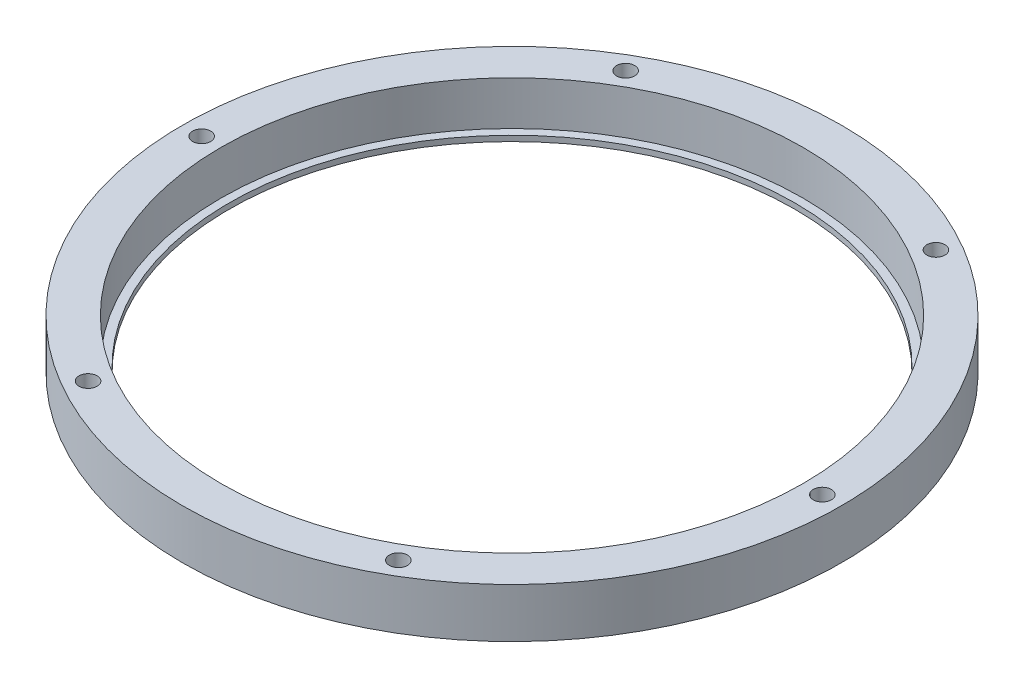
SolidWorks part; units mm, degrees
material "6061 合金"
ref_plane "前视基准面" through (0, 0, 0) normal (0, 0, 1) x (1, 0, 0)
ref_plane "上视基准面" through (0, 0, 0) normal (0, 1, 0) x (1, 0, 0)
ref_plane "右视基准面" through (0, 0, 0) normal (1, 0, 0) x (0, 0, -1)
sketch "草图2" plane through (0, 0, 0) normal (0, 1, 0) x (1, 0, 0)
  circle A0 centre (0, 0) radius 60
  circle A1 centre (0, 0) radius 53
  dimension "D1" = 7
  dimension "D2" = 106
extrude "凸台-拉伸1" add sketch "草图2" along normal blind 8
sketch "草图3" plane through (0, 0, 0) normal (0, -1, 0) x (1, 0, 0)
  circle A0 centre (0, 0) radius 51.5
  circle A1 centre (0, 0) radius 60
  circle A2 centre (0, 0) radius 60
  circle A3 centre (0, 0) radius 53 construction
  dimension "D2" = 1.5
  dimension "D1" = 0
extrude "凸台-拉伸2" add sketch "草图3" along normal blind 1
hole_wizard "M4 螺纹孔1" positions "草图4" profile "草图5" tap size "M4" standard "GB" end condition through all
sketch "草图4" plane through (0, 8, 0) normal (0, 1, 0) x (1, 0, 0)
  circle A0 centre (0, 0) radius 56.5 construction
  circle A1 centre (0, 0) radius 60 construction
  point P0 (-28.25, 48.9304)
  point P25 (28.25, 48.9304)
  point P26 (56.5, 0)
  point P27 (28.25, -48.9304)
  point P28 (-28.25, -48.9304)
  point P29 (-56.5, 0)
  point P31 (22.4829, 51.834)
  point P32 (46.7788, 31.6858)
  point P33 (52.3877, 21.1607)
  point P34 (0, 0)
  dimension "D1" = 3.5
  dimension "D2" = 6
sketch "草图5" plane through (-28.25, 8, -48.9304) normal (1, 0, 0) x (0, 0, 1)
  line L0 (0, 0) -> (0, 9)
  line L1 (0, 9) -> (1.65, 9)
  line L2 (1.65, 9) -> (1.65, 0)
  line L5 (1.65, 0) -> (0, 0)
  line L11 (0, -6.35) -> (0, 107.95) construction
  dimension "通孔螺纹孔钻头直径" = 3.3
  dimension "通孔螺纹孔钻头深度" = 9
cosmetic thread "孔螺蚊线1" parameters "D1"=12, "D2"=4.3
cosmetic thread "孔螺蚊线2" parameters "D1"=12, "D2"=4.3
cosmetic thread "孔螺蚊线3" parameters "D1"=12, "D2"=4.3
cosmetic thread "孔螺蚊线4" parameters "D1"=12, "D2"=4.3
cosmetic thread "孔螺蚊线5" parameters "D1"=12, "D2"=4.3
cosmetic thread "孔螺蚊线6" parameters "D1"=9, "D2"=4.3
